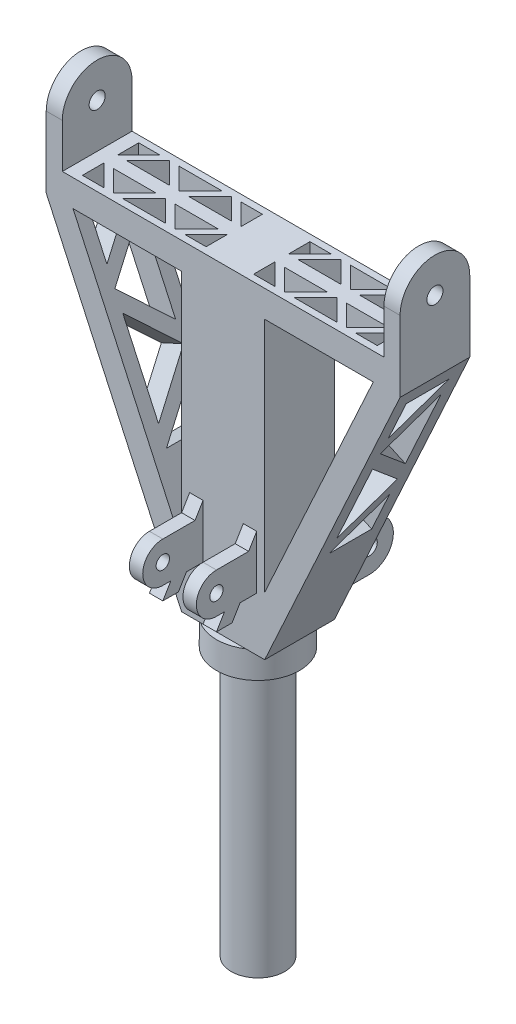
SolidWorks part; units mm, degrees
ref_plane "Front Plane" through (0, 0, 0) normal (0, 0, 1) x (1, 0, 0)
ref_plane "Top Plane" through (0, 0, 0) normal (0, 1, 0) x (1, 0, 0)
ref_plane "Right Plane" through (0, 0, 0) normal (1, 0, 0) x (0, 0, -1)
sketch "Sketch27" plane through (0, 0, 0) normal (0, 0, 1) x (1, 0, 0)
  line L0 (66, -50) -> (-66, -50)
  line L1 (-66, -50) -> (-66, 100)
  line L2 (-66, 100) -> (-60, 100)
  line L3 (-60, 100) -> (-60, 70)
  line L4 (-60, 70) -> (60, 70)
  line L5 (0, -50) -> (0, 82.1741) construction
  line L6 (60, 100) -> (60, 70)
  line L7 (66, 100) -> (60, 100)
  line L8 (66, -50) -> (66, 100)
  point P10 (0, -50)
  point P11 (0, 70)
  point P13 (0, 0)
  dimension "D1" = 120
  dimension "D2" = 6
  dimension "D3" = 150
  dimension "D4" = 30
extrude "Tykkelse leddfester og bredde/høyde selve modellen" add sketch "Sketch27" along normal mid plane 26
sketch "Sketch28" plane through (0, -50, 0) normal (0, -1, 0) x (1, 0, 0)
  line L0 (-66, -13) -> (66, -13) construction
  line L1 (66, 13) -> (66, -13) construction
  circle A1 centre (0, 0) radius 10.5
  circle A2 centre (0, 0) radius 15.5
  point P6 (0, -13)
  point P9 (66, 0)
  dimension "D1" = 21
  dimension "D2" = 5
extrude "Hull til lårben/karbonfiberrør" add sketch "Sketch28" along normal blind 10
sketch "Sketch29" plane through (66, 0, 0) normal (1, 0, 0) x (0, 0, -1)
  line L0 (-13, 100) -> (13, 100) construction
  line L1 (-13, 86.5) -> (-13, 71.5)
  line L2 (13, 86.5) -> (13, 71.5)
  line L4 (-14, 101) -> (0, 101)
  line L8 (0, 86.5) -> (0, 83.5) construction
  line L9 (0, 100) -> (0, 99.5) construction
  line L13 (-13, 71.5) -> (-14, 71.5)
  line L14 (-14, 71.5) -> (-14, 101)
  line L18 (13, 71.5) -> (14, 71.5)
  line L19 (14, 71.5) -> (14, 101)
  line L20 (14, 101) -> (0, 101)
  circle A0 centre (0, 86.5) radius 3
  arc A1 (13, 86.5) -> (-13, 86.5) centre (0, 86.5) ccw
  circle A2 centre (0, 86.5) radius 13 construction
  point P4 (0, 100)
  point P14 (-7, 101)
  dimension "D1" = 6
  dimension "D3" = 15
  dimension "D4" = 0.5
  dimension "D5" = 1
  dimension "D6" = 1
  dimension "D2" = 10
extrude "Skruehull leddfester" cut sketch "Sketch29" against normal through all both and the other way through all
sketch "Fasong (mønster på selve kroppen)" plane through (0, 0, 13) normal (0, 0, 1) x (1, 0, 0)
  line L0 (-66, 60) -> (-15.5, -50)
  line L1 (-66, 86.5) -> (-66, -50) construction
  line L2 (-15.5, -50) -> (-66, -50)
  line L3 (-66, -50) -> (-66, 60)
  line L4 (-60, 70) -> (-66, 70) construction
  line L5 (0, 0) -> (0, 49.2612) construction
  line L6 (15.5, -50) -> (66, -50)
  line L7 (66, 60) -> (15.5, -50)
  line L8 (66, -50) -> (66, 60)
  line L9 (-15.5, -50) -> (-15.5, 60) construction
  line L11 (15.5, -50) -> (15.5, 60) construction
  line L12 (-66, 60) -> (-56, 60) construction
  line L13 (-56, 60) -> (-15.5, -28.2178)
  line L14 (-56, 60) -> (-15.5, 60)
  line L15 (-15.5, 60) -> (-15.5, -28.2178)
  line L16 (56, 60) -> (15.5, 60)
  line L17 (56, 60) -> (15.5, -28.2178)
  line L18 (15.5, 60) -> (15.5, -28.2178)
  dimension "D1" = 10
  dimension "D2" = 10
  dimension "D3" = 31
sketch "Sketch33" plane through (0, 0, -13) normal (0, 0, -1) x (-1, 0, 0)
  line L4 (8.441, -50) -> (-8.441, -50) construction
  line L5 (-3.5, -30) -> (-3.5, -50)
  line L6 (-3.5, -50) -> (-8.5, -50)
  line L7 (-8.5, -50) -> (-8.5, -30)
  line L8 (-8.5, -30) -> (-3.5, -30)
  line L9 (0, 0) -> (0, 33.6157) construction
  line L10 (0, 0) -> (0, 49.2612) construction
  line L11 (8.5, -50) -> (8.5, -30)
  line L12 (3.5, -50) -> (8.5, -50)
  line L13 (3.5, -30) -> (3.5, -50)
  line L14 (8.5, -30) -> (3.5, -30)
  dimension "D1" = 5
  dimension "D2" = 20
  dimension "D3" = 7
extrude "Bredde og avstand stempelende" add sketch "Sketch33" along normal blind 60
sketch "Rod-ende, justere lengden (altså feste til største sylinder)" plane through (8.5, 0, 0) normal (1, 0, 0) x (0, 0, -1)
  line L0 (13, -30) -> (13, -50) construction
  line L5 (43, -51) -> (74, -51)
  line L6 (74, -51) -> (74, -29)
  line L7 (74, -29) -> (43, -29)
  line L9 (73, -50) -> (13, -50) construction
  line L11 (73, -30) -> (73, -50) construction
  line L12 (73, -30) -> (13, -30) construction
  line L13 (33, -49) -> (13, -49)
  line L14 (13, -50) -> (13, 86.5) construction
  line L15 (13, -49) -> (13, -51)
  line L16 (13, -51) -> (43, -51)
  line L17 (43, -29) -> (13, -29)
  line L18 (13, -29) -> (13, -31)
  line L19 (13, -31) -> (33, -31)
  circle A0 centre (33, -40) radius 3
  arc A1 (33, -49) -> (33, -31) centre (33, -40) ccw
  circle A2 centre (33, -40) radius 9 construction
  point P6 (13, -40)
  dimension "D1" = 6
  dimension "D3" = 20
  dimension "D4" = 1
  dimension "D5" = 1
  dimension "D6" = 1
  dimension "D2" = 6
sketch "Sketch39" plane through (0, 0, 13) normal (0, 0, 1) x (1, 0, 0)
  line L8 (-12.5, -15) -> (-12.5, -30)
  line L9 (-12.5, -15) -> (-7.5, -15)
  line L10 (-7.5, -15) -> (-7.5, -30)
  line L11 (0, 0) -> (0, 49.2612) construction
  line L12 (0, 0) -> (0, 21.5969) construction
  line L18 (-7.5, -30) -> (-12.5, -30)
  line L19 (-66, -50) -> (-8.441, -50) construction
  line L20 (7.5, -15) -> (7.5, -30)
  line L21 (12.5, -15) -> (7.5, -15)
  line L22 (12.5, -15) -> (12.5, -30)
  line L23 (7.5, -30) -> (12.5, -30)
  dimension "D1" = 15
  dimension "D2" = 5
  dimension "D3" = 20
  dimension "D4" = 7.5
extrude "Cut-Extrude4" cut sketch "Fasong (mønster på selve kroppen)" against normal through all
sketch "Sketch40" plane through (-31.7606, -14.581, 0) normal (-0.9088, -0.4172, 0) x (0, 0, 1)
  line L0 (0, 82.065) -> (0, 35.3376) construction
  line L1 (-13, 82.065) -> (13, 82.065) construction
  line L2 (-8, 75.565) -> (8, 75.565)
  line L3 (-13, -38.9732) -> (-13, 82.065) construction
  line L4 (-8, 75.565) -> (8, 59.565)
  line L6 (-8, 68.4939) -> (8, 52.4939)
  line L8 (-8, 36.4939) -> (8, 52.4939)
  line L9 (8, 75.565) -> (8, 59.565)
  line L10 (-8, 36.4939) -> (-8, 68.4939)
  line L13 (8, 13.4229) -> (-8, 29.4229)
  line L16 (8, 45.4229) -> (-8, 29.4229)
  line L18 (8, 13.4229) -> (8, 45.4229)
  line L19 (-8, 22.3518) -> (8, 6.3518)
  line L20 (8, 6.3518) -> (-8, 6.3518)
  line L21 (-8, 6.3518) -> (-8, 22.3518)
  line L22 (-13, -38.9732) -> (0, -38.9732) construction
  point P8 (0, 75.565)
  dimension "D1" = 6.5
  dimension "D2" = 5
  dimension "D3" = 45
  dimension "D4" = 90
  dimension "D5" = 5
  dimension "D6" = 5
  dimension "D7" = 90
  dimension "D8" = 5
  dimension "D9" = 45.325
extrude "Sidemønster" cut sketch "Sketch40" against normal up to vertex (9.088 mm away)
sketch "Sketch42" plane through (31.7606, -14.581, 0) normal (0.9088, -0.4172, 0) x (0, 0, -1)
  line L3 (0, 82.065) -> (0, 75.565) construction
  line L4 (13, 82.065) -> (-13, 82.065) construction
  line L5 (8, 75.565) -> (-8, 75.565)
  line L6 (-13, 82.065) -> (-13, -38.9732) construction
  line L7 (-8, 75.565) -> (-8, 59.565)
  line L8 (-8, 59.565) -> (8, 75.565)
  line L9 (8, 68.4939) -> (-8, 52.4939)
  line L11 (8, 36.4939) -> (8, 68.4939)
  line L12 (8, 36.4939) -> (-8, 52.4939)
  line L13 (-8, 45.4229) -> (8, 29.4229)
  line L15 (-8, 13.4229) -> (-8, 45.4229)
  line L16 (-8, 13.4229) -> (8, 29.4229)
  line L17 (8, 22.3518) -> (-8, 6.3518)
  line L18 (-8, 6.3518) -> (8, 6.3518)
  line L19 (8, 6.3518) -> (8, 22.3518)
  point P8 (0, 82.065)
  point P11 (0, 75.565)
  dimension "D1" = 6.5
  dimension "D2" = 5
  dimension "D3" = 45
  dimension "D4" = 5
  dimension "D5" = 45
  dimension "D6" = 45
  dimension "D7" = 5
  dimension "D9" = 5
extrude "Sidemønster 2" cut sketch "Sketch42" against normal up to vertex (9.088 mm away)
sketch "Sketch44" plane through (0, -50, 0) normal (0, -1, 0) x (1, 0, 0)
  circle A0 centre (0, 0) radius 10.5
  dimension "D1" = 21
extrude "Utvidet lårbenhull inn i selve kroppen" cut sketch "Sketch44" against normal blind 60
sketch "Sketch45" plane through (0, 70, 0) normal (0, 1, 0) x (1, 0, 0)
  line L3 (-39.9289, 10.5) -> (-31.9289, 2.5)
  line L5 (-23.9289, 10.5) -> (-39.9289, 10.5)
  line L6 (-16.8579, 10.5) -> (-8.8579, 2.5)
  line L7 (0, 0) -> (0, 11.265) construction
  line L8 (0, 0) -> (-55, 0) construction
  line L9 (-60, -13) -> (-60, 13) construction
  line L10 (-55, 2.5) -> (-55, 10.5)
  line L11 (-55, 10.5) -> (-47, 10.5)
  line L12 (-47, 10.5) -> (-55, 2.5)
  line L13 (60, 13) -> (-60, 13) construction
  line L14 (-43.4645, 10.5) -> (-51.4645, 2.5)
  line L15 (-51.4645, 2.5) -> (-35.4645, 2.5)
  line L17 (-43.4645, 10.5) -> (-35.4645, 2.5)
  line L18 (-23.9289, 10.5) -> (-31.9289, 2.5)
  line L19 (-20.3934, 10.5) -> (-28.3934, 2.5)
  line L20 (-28.3934, 2.5) -> (-12.3934, 2.5)
  line L22 (-20.3934, 10.5) -> (-12.3934, 2.5)
  line L23 (-8.8579, 2.5) -> (-8.8579, 10.5)
  line L24 (-8.8579, 10.5) -> (-16.8579, 10.5)
  line L25 (-8.8579, -2.5) -> (-8.8579, -10.5)
  line L26 (-16.8579, -10.5) -> (-8.8579, -2.5)
  line L27 (-8.8579, -10.5) -> (-16.8579, -10.5)
  line L28 (-20.3934, -10.5) -> (-12.3934, -2.5)
  line L29 (-28.3934, -2.5) -> (-12.3934, -2.5)
  line L30 (-20.3934, -10.5) -> (-28.3934, -2.5)
  line L31 (-23.9289, -10.5) -> (-31.9289, -2.5)
  line L32 (-23.9289, -10.5) -> (-39.9289, -10.5)
  line L33 (-39.9289, -10.5) -> (-31.9289, -2.5)
  line L34 (-43.4645, -10.5) -> (-35.4645, -2.5)
  line L35 (-51.4645, -2.5) -> (-35.4645, -2.5)
  line L36 (-43.4645, -10.5) -> (-51.4645, -2.5)
  line L37 (-55, -10.5) -> (-47, -10.5)
  line L38 (-55, -2.5) -> (-55, -10.5)
  line L39 (-47, -10.5) -> (-55, -2.5)
  line L40 (8.8579, 2.5) -> (8.8579, 10.5)
  line L41 (16.8579, 10.5) -> (8.8579, 2.5)
  line L42 (8.8579, 10.5) -> (16.8579, 10.5)
  line L43 (16.8579, -10.5) -> (8.8579, -2.5)
  line L44 (8.8579, -10.5) -> (16.8579, -10.5)
  line L45 (8.8579, -2.5) -> (8.8579, -10.5)
  line L46 (20.3934, -10.5) -> (28.3934, -2.5)
  line L47 (28.3934, -2.5) -> (12.3934, -2.5)
  line L48 (20.3934, -10.5) -> (12.3934, -2.5)
  line L49 (20.3934, 10.5) -> (12.3934, 2.5)
  line L50 (28.3934, 2.5) -> (12.3934, 2.5)
  line L51 (20.3934, 10.5) -> (28.3934, 2.5)
  line L52 (23.9289, 10.5) -> (31.9289, 2.5)
  line L53 (23.9289, 10.5) -> (39.9289, 10.5)
  line L54 (39.9289, 10.5) -> (31.9289, 2.5)
  line L55 (23.9289, -10.5) -> (39.9289, -10.5)
  line L56 (39.9289, -10.5) -> (31.9289, -2.5)
  line L57 (23.9289, -10.5) -> (31.9289, -2.5)
  line L58 (43.4645, -10.5) -> (51.4645, -2.5)
  line L59 (51.4645, -2.5) -> (35.4645, -2.5)
  line L60 (43.4645, -10.5) -> (35.4645, -2.5)
  line L61 (55, -2.5) -> (55, -10.5)
  line L62 (47, -10.5) -> (55, -2.5)
  line L63 (55, -10.5) -> (47, -10.5)
  line L64 (43.4645, 10.5) -> (35.4645, 2.5)
  line L65 (51.4645, 2.5) -> (35.4645, 2.5)
  line L66 (43.4645, 10.5) -> (51.4645, 2.5)
  line L67 (55, 10.5) -> (47, 10.5)
  line L68 (55, 2.5) -> (55, 10.5)
  line L69 (47, 10.5) -> (55, 2.5)
  dimension "D1" = 5
  dimension "D2" = 2.5
  dimension "D3" = 2.5
  dimension "D4" = 45
  dimension "D5" = 2.5
  dimension "D6" = 45
  dimension "D7" = 2.5
  dimension "D8" = 45
  dimension "D9" = 2.5
  dimension "D10" = 45
  dimension "D11" = 2.5
extrude "Mønster topp" cut sketch "Sketch45" against normal up to vertex (10 mm away)
extrude "Stempelende av største sylinder " cut sketch "Rod-ende, justere lengden (altså feste til største sylinder)" against normal through all both and the other way through all
extrude "Sylinderfeste, selve den lille sylinderen " add sketch "Sketch39" along normal blind 25
sketch "Sketch46" plane through (8.5, 0, 0) normal (1, 0, 0) x (0, 0, -1)
  line L2 (13, 60) -> (13, -50) construction
  line L3 (13, -14.0039) -> (26.5969, -31)
  line L4 (33, -31) -> (13, -31) construction
  line L5 (26.5969, -31) -> (33, -31)
  line L6 (33, -31) -> (13, -6)
  line L7 (13, -6) -> (13, -14.0039)
  line M3 (33, -31) -> (13, -31)
  dimension "D1" = 5
  dimension "D2" = 25
extrude "Støtter største sylinder 1" add sketch "Sketch46" against normal blind 5 contours L6 L7 L3 M3
sketch "Sketch47" plane through (-8.5, 0, 0) normal (-1, 0, 0) x (0, 0, 1)
  line L0 (-33, -31) -> (-13, -6)
  line L1 (-13, -50) -> (-13, 60) construction
  line L2 (-13, -6) -> (-13, -14.0039) construction
  line L3 (-13, -6) -> (-13, -14.0039)
  line L4 (-13, -14.0039) -> (-26.5969, -31)
  line L5 (-13, -31) -> (-33, -31) construction
  line L6 (-13, -14.0039) -> (-26.5969, -31) construction
  line L7 (-26.5969, -31) -> (-33, -31)
extrude "Støtter største sylinder 2" add sketch "Sketch47" against normal blind 5
sketch "Sketch48" plane through (-12.5, 0, 0) normal (-1, 0, 0) x (0, 0, 1)
  line L1 (28, -30) -> (13.1798, -30)
  line L2 (13.1798, -30) -> (13.1798, -31)
  line L3 (13.1798, -31) -> (39, -31)
  line L4 (39, -31) -> (39, -14)
  line L5 (39, -14) -> (13, -14)
  line L6 (13, -50) -> (13, 60) construction
  line L7 (13, -14) -> (13, -15)
  line L8 (13, -15) -> (28, -15)
  line L13 (38, -15) -> (38, -30) construction
  circle A0 centre (28, -22.5) radius 2.5
  arc A1 (28, -30) -> (28, -15) centre (28, -22.5) ccw
  circle A2 centre (28, -22.5) radius 7.5 construction
  point P3 (0, 0)
  point P10 (0, 0)
  point P11 (0, 0)
  point P20 (0, 0)
  point P22 (0, 0)
  point P26 (13, -12.2256)
  point P27 (38, -22.5)
  point P28 (0, 0)
  dimension "D1" = 5
  dimension "D3" = 1
  dimension "D4" = 1
  dimension "D2" = 5
extrude "Sylinderfeste, liten sylinder" cut sketch "Sketch48" against normal through all both and the other way through all
sketch "Sketch49" plane through (-12.5, 0, 0) normal (-1, 0, 0) x (0, 0, 1)
  line L0 (28, -35) -> (13, -10)
  line L1 (13, -50) -> (13, 60) construction
  line L2 (13, -10) -> (13, -19.7183)
  line L3 (22.169, -35) -> (28, -35)
  line L4 (13, -19.7183) -> (22.169, -35)
  dimension "D1" = 25
  dimension "D2" = 5
sketch "Sketch50" plane through (12.5, 0, 0) normal (1, 0, 0) x (0, 0, -1)
  line L0 (-28, -35) -> (-22.169, -35)
  line L1 (-22.169, -35) -> (-13, -19.7183)
  line L2 (-13, -19.7183) -> (-13, -10)
  line L3 (-13, -10) -> (-28, -35)
extrude "Boss-Extrude11" add sketch "Sketch49" against normal blind 5
extrude "Boss-Extrude12" add sketch "Sketch50" against normal blind 5 contours L3 L0 L1 L2
sketch "Sketch51" plane through (0, 10, 0) normal (0, -1, 0) x (1, 0, 0)
  circle A0 centre (0, 0) radius 10
  dimension "D1" = 20
extrude "TIL ASSEMBLY - SLETT FØR PRINTING" add sketch "Sketch51" along normal blind 170
